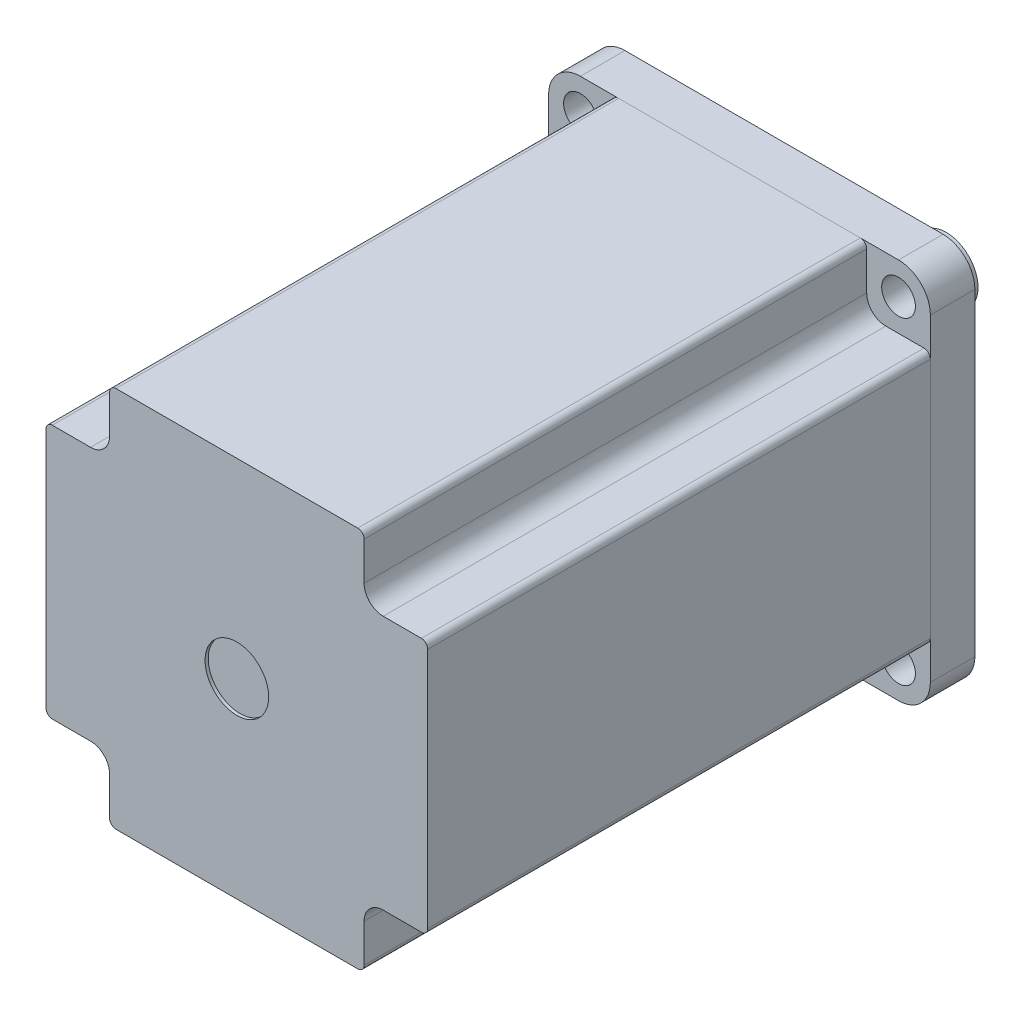
SolidWorks part; units mm, degrees
material "SKD11淬火HRC56-60"
ref_plane "前基準面" through (0, 0, 0) normal (0, 0, 1) x (1, 0, 0)
ref_plane "上基準面" through (0, 0, 0) normal (0, 1, 0) x (1, 0, 0)
ref_plane "右基準面" through (0, 0, 0) normal (1, 0, 0) x (0, 0, -1)
sketch "草图1" plane through (0, 0, 0) normal (0, 0, 1) x (1, 0, 0)
  line L1 (0, 0) -> (60, 0)
  line L2 (0, 0) -> (0, 60)
  line L3 (0, 60) -> (60, 60)
  line L4 (60, 0) -> (60, 60)
  dimension "D1" = 60
extrude "凸台-拉伸1" add sketch "草图1" along normal blind 7
fillet "圆角1" radius 5 4 edges at (60, 0, 3.5) (0, 0, 3.5) (0, 60, 3.5) (60, 60, 3.5)
sketch "草图3" plane through (0, 0, 0) normal (0, 0, -1) x (-1, 0, 0)
  line L0 (-30, 60) -> (-30, 0) construction
  line L1 (-55, 60) -> (-5, 60) construction
  line L2 (-5, 0) -> (-55, 0) construction
  line L3 (-60, 30) -> (0, 30) construction
  line L4 (-60, 5) -> (-60, 55) construction
  line L5 (0, 55) -> (0, 5) construction
  circle A0 centre (-55, 55) radius 2.65
  circle A1 centre (-5, 55) radius 2.65
  circle A2 centre (-5, 5) radius 2.65
  circle A3 centre (-55, 5) radius 2.65
  dimension "D1" = 5.3
  dimension "D2" = 50
  dimension "D3" = 50
extrude "切除-拉伸1" cut sketch "草图3" against normal through all
sketch "草图4" plane through (0, 0, 7) normal (0, 0, 1) x (1, 0, 0)
  line L0 (60, 5) -> (60, 55) construction
  line L1 (0, 60) -> (60, 60)
  line L2 (0, 60) -> (0, 0)
  line L3 (0, 0) -> (60, 0)
  line L4 (60, 60) -> (60, 0)
  line L5 (5, 0) -> (55, 0) construction
  line L6 (0, 55) -> (0, 5) construction
  line L7 (55, 60) -> (5, 60) construction
extrude "凸台-拉伸2" add sketch "草图4" along normal blind 79 separate body
sketch "草图5" plane through (0, 0, 86) normal (0, 0, 1) x (1, 0, 0)
  line L0 (30, 60) -> (30, 0) construction
  line L1 (0, 60) -> (10, 60)
  line L2 (0, 60) -> (0, 50)
  line L3 (0, 50) -> (10, 50)
  line L4 (10, 60) -> (10, 50)
  line L5 (60, 60) -> (0, 60) construction
  line L6 (0, 0) -> (60, 0) construction
  line L7 (0, 30) -> (60, 30) construction
  line L8 (0, 60) -> (0, 0) construction
  line L9 (60, 0) -> (60, 60) construction
  line L10 (10, 0) -> (10, 10)
  line L11 (0, 10) -> (10, 10)
  line L12 (0, 0) -> (0, 10)
  line L13 (0, 0) -> (10, 0)
  line L14 (60, 0) -> (50, 0)
  line L15 (60, 0) -> (60, 10)
  line L16 (60, 10) -> (50, 10)
  line L17 (50, 0) -> (50, 10)
  line L18 (50, 60) -> (50, 50)
  line L19 (60, 50) -> (50, 50)
  line L20 (60, 60) -> (60, 50)
  line L21 (60, 60) -> (50, 60)
  dimension "D1" = 40
extrude "切除-拉伸2" cut sketch "草图5" against normal up to surface (79 mm away) up to face at (30, 30, 7)
fillet "圆角2" radius 3 4 edges at (50, 10, 46.5) (10, 10, 46.5) (10, 50, 46.5) (50, 50, 46.5)
fillet "圆角3" radius 1 8 edges at (60, 50, 46.5) (50, 60, 46.5) (10, 60, 46.5) (0, 50, 46.5) (0, 10, 46.5) (10, 0, 46.5) (50, 0, 46.5) (60, 10, 46.5)
sketch "草图6" plane through (0, 0, 86) normal (0, 0, 1) x (1, 0, 0)
  line L0 (30, 0) -> (30, 60) construction
  line L1 (11, 0) -> (49, 0) construction
  line L2 (49, 60) -> (11, 60) construction
  circle A0 centre (30, 30) radius 5
  dimension "D1" = 10
extrude "切除-拉伸3" cut sketch "草图6" against normal blind 0.5
sketch "草图7" plane through (0, 0, 0) normal (0, 0, -1) x (-1, 0, 0)
  line L0 (-30, 0) -> (-30, 60) construction
  line L1 (-5, 0) -> (-55, 0) construction
  line L2 (-55, 60) -> (-5, 60) construction
  circle A0 centre (-30, 30) radius 18
  dimension "D1" = 36
extrude "凸台-拉伸3" add sketch "草图7" along normal blind 1.5
sketch "草图8" plane through (0, 0, -1.5) normal (0, 0, -1) x (-1, 0, 0)
  circle A0 centre (-30, 30) radius 5
  dimension "D1" = 10
extrude "凸台-拉伸4" add sketch "草图8" along normal blind 24
sketch "草图9" plane through (0, 0, 0) normal (0, -1, 0) x (1, 0, 0)
  line L0 (30, 86) -> (30, 57.2143) construction
  line L1 (25, 75) -> (35, 75)
  line L2 (25, 75) -> (25, 83)
  line L3 (25, 83) -> (35, 83)
  line L4 (35, 75) -> (35, 83)
  line L5 (11, 86) -> (49, 86) construction
  dimension "D1" = 10
  dimension "D2" = 8
  dimension "D3" = 3
extrude "凸台-拉伸5" add sketch "草图9" along normal blind 2
